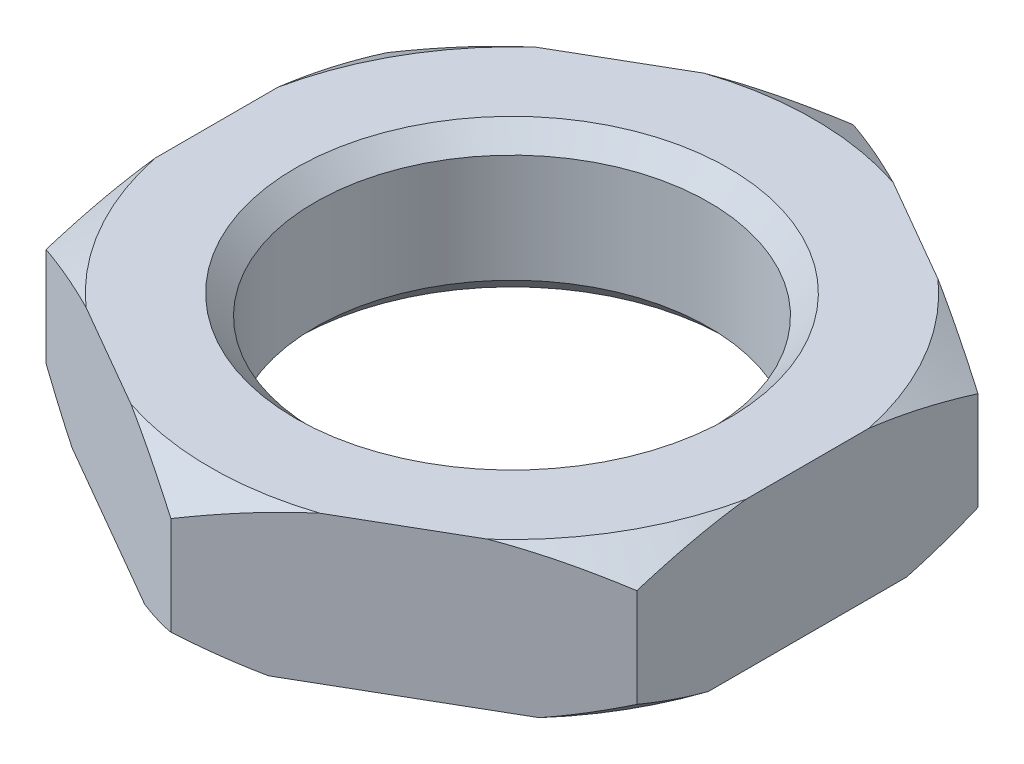
SolidWorks part; units mm, degrees
ref_plane "Front Plane" through (0, 0, 0) normal (0, 0, 1) x (1, 0, 0)
ref_plane "Top Plane" through (0, 0, 0) normal (0, 1, 0) x (1, 0, 0)
ref_plane "Right Plane" through (0, 0, 0) normal (1, 0, 0) x (0, 0, -1)
sketch "Sketch1" plane through (0, 0, 0) normal (0, 1, 0) x (1, 0, 0)
  line L1 (0, -3.4641) -> (3, -1.7321)
  line L2 (3, -1.7321) -> (3, 1.7321)
  line L3 (3, 1.7321) -> (0, 3.4641)
  line L4 (0, 3.4641) -> (-3, 1.7321)
  line L5 (-3, 1.7321) -> (-3, -1.7321)
  line L6 (-3, -1.7321) -> (0, -3.4641)
  circle A0 centre (0, 0) radius 3 construction
  dimension "D1" = 6
extrude "Boss-Extrude1" add sketch "Sketch1" along normal blind 1.5
sketch "Sketch2" plane through (0, 1.5, 0) normal (0, 1, 0) x (1, 0, 0)
  circle A0 centre (0, 0) radius 2
extrude "Cut-Extrude1" cut sketch "Sketch2" against normal through all
chamfer "Chamfer1" distance 0.2 angle 45 2 edges at (0, 1.5, 2) (0, 0, 2)
sketch "Sketch3" plane through (0, 0, 0) normal (1, 0, 0) x (0, 0, -1)
  line L0 (0, 3.372) -> (0, -0.8345) construction
  line L1 (-3.4641, 1.5) -> (-3.4641, 1.25)
  line L2 (-3.4641, 1.5) -> (-3.4641, 0) construction
  line L3 (-3.4641, 1.25) -> (-3.0641, 1.5)
  line L4 (-3.4641, 1.5) -> (-1.7321, 1.5) construction
  line L5 (-3.1641, 0) -> (-3.4641, 0.25)
  line L6 (-3.4641, 0) -> (-1.7321, 0) construction
  line L7 (-3.4641, 0.25) -> (-3.4641, 0)
  line L8 (-3.0641, 1.5) -> (-3.4641, 1.5)
  line L9 (-3.1641, 0) -> (-3.4641, 0)
  dimension "D1" = 0.4
  dimension "D2" = 0.25
  dimension "D3" = 0.3
  dimension "D4" = 0.25
revolve "Cut-Revolve3" cut sketch "Sketch3" angle 360 about L0
